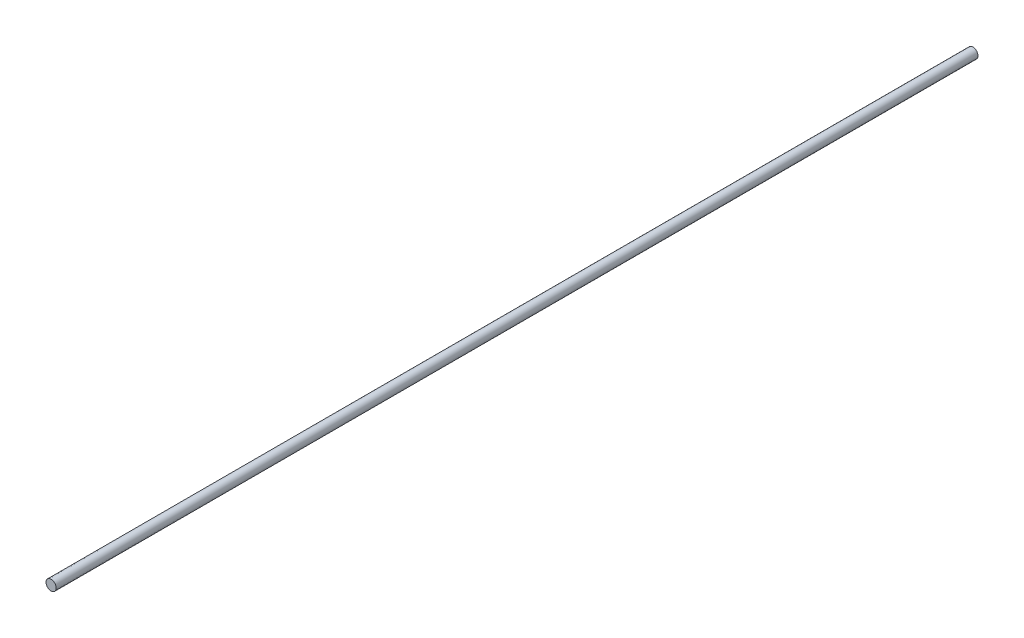
SolidWorks part; units mm, degrees
ref_plane "前视基准面" through (0, 0, 0) normal (0, 0, 1) x (1, 0, 0)
ref_plane "上视基准面" through (0, 0, 0) normal (0, 1, 0) x (1, 0, 0)
ref_plane "右视基准面" through (0, 0, 0) normal (1, 0, 0) x (0, 0, -1)
sketch "草图1" plane through (0, 0, 0) normal (0, 0, 1) x (1, 0, 0)
  circle A0 centre (0, 0) radius 2.2
  dimension "D1" = 4.4
extrude "凸台-拉伸1" add sketch "草图1" along normal blind 400
